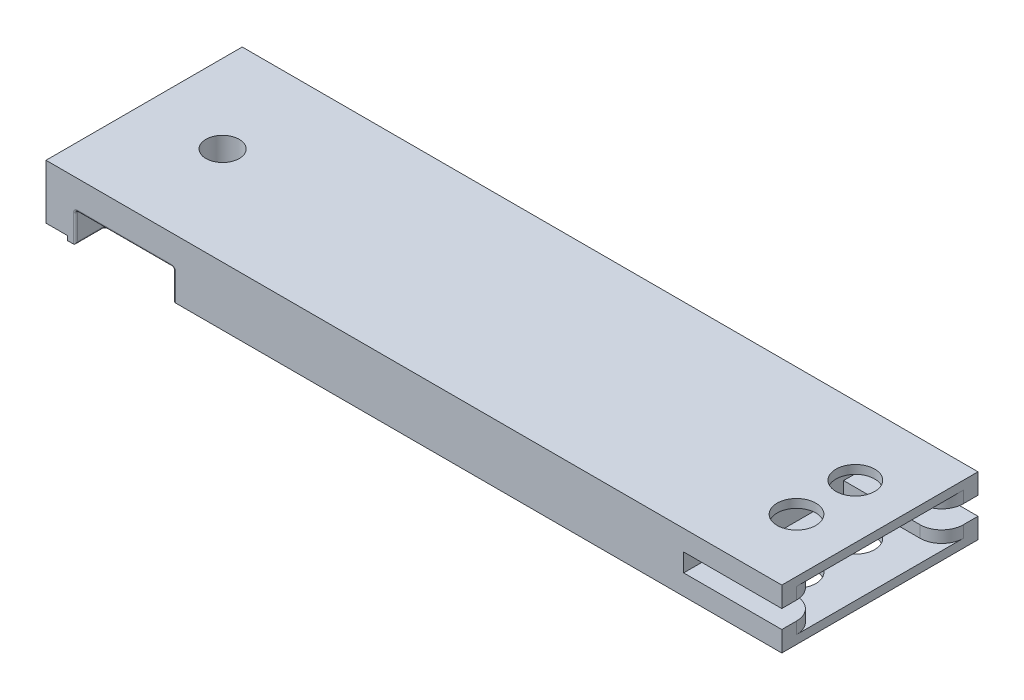
SolidWorks part; units mm, degrees
ref_plane "Front Plane" through (0, 0, 0) normal (0, 0, 1) x (1, 0, 0)
ref_plane "Top Plane" through (0, 0, 0) normal (0, 1, 0) x (1, 0, 0)
ref_plane "Right Plane" through (0, 0, 0) normal (1, 0, 0) x (0, 0, -1)
sketch "Sketch1" plane through (0, 0, 0) normal (1, 0, 0) x (0, 0, -1)
  line L1 (-10, -6) -> (10, -6)
  line L2 (-10, -6) -> (-10, 0)
  line L3 (-10, 0) -> (10, 0)
  line L4 (10, -6) -> (10, 0)
  line L5 (-10, -6) -> (10, 0) construction
  line L6 (-10, 0) -> (10, -6) construction
  point P0 (0, -3)
  dimension "D1" = 20
  dimension "D2" = 6
extrude "Boss-Extrude1" add sketch "Sketch1" along normal blind 75
hole_wizard "M3 Clearance Hole1" positions "Sketch2" profile "Sketch3" hole size "M3" standard "ISO" end condition through all
sketch "Sketch2" plane through (0, 0, 0) normal (0, 1, 0) x (1, 0, 0)
  line L0 (0, 10) -> (0, -10) construction
  point P0 (8, 0)
  dimension "D1" = 8
sketch "Sketch3" plane through (8, 0, 0) normal (1, 0, 0) x (0, 0, 1)
  line L0 (0, 0) -> (0, 6)
  line L1 (0, 6) -> (1.7, 6)
  line L2 (1.7, 6) -> (1.7, 0)
  line L5 (1.7, 0) -> (0, 0)
  line L11 (0, -6.35) -> (0, 107.95) construction
  dimension "Thru Hole Dia." = 3.4
  dimension "Thru Hole Depth" = 6
sketch "Sketch4" plane through (0, 0, 0) normal (0, 1, 0) x (1, 0, 0)
  line L13 (75, 10) -> (75, -10) construction
  circle A0 centre (69.5, 3) radius 1.975
  circle A1 centre (69.5, -3) radius 1.975
  point P10 (69.5, -3)
  point P18 (69.5, 3)
  dimension "D5" = 3.95
  dimension "D6" = 3.95
  dimension "D1" = 5.5
  dimension "D2" = 6
  dimension "D3" = 3
extrude "Cut-Extrude1" cut sketch "Sketch4" against normal through all
sketch "Sketch5" plane through (75, 0, 0) normal (1, 0, 0) x (0, 0, -1)
  line L0 (10, -6) -> (10, 0) construction
  line L1 (-10, -3.925) -> (-6.3, -3.925)
  line L2 (-10, -3.925) -> (-10, -2.075)
  line L3 (-10, -2.075) -> (-6.3, -2.075)
  line L4 (10, -3.925) -> (10, -2.075)
  line L7 (-10, 0) -> (-10, -6) construction
  line L8 (-6.3, -5.125) -> (6.3, -5.125)
  line L9 (-6.3, -5.125) -> (-6.3, -3.925)
  line L10 (-6.3, -0.875) -> (6.3, -0.875)
  line L11 (6.3, -5.125) -> (6.3, -3.925)
  line L15 (-6.3, -2.075) -> (-6.3, -0.875)
  line L18 (6.3, -2.075) -> (10, -2.075)
  line L20 (6.3, -3.925) -> (10, -3.925)
  line L21 (6.3, -2.075) -> (6.3, -0.875)
  point P0 (0, -3)
  point P7 (0, -3)
  point P12 (10, -3)
  point P17 (-10, -3)
  dimension "D1" = 12.6
  dimension "D2" = 1.85
  dimension "D3" = 3
  dimension "D4" = 4.25
extrude "Cut-Extrude2" cut sketch "Sketch5" against normal blind 10
sketch "Sketch6" plane through (0, -6, 0) normal (0, -1, 0) x (1, 0, 0)
  line L0 (75, 10) -> (0, 10) construction
  line L1 (3, 10) -> (13, 10)
  line L2 (3, 10) -> (3, 7)
  line L3 (3, 7) -> (13, 7)
  line L4 (13, 10) -> (13, 7)
  line L5 (75, -10) -> (0, -10) construction
  line L6 (13, -10) -> (3, -10)
  line L7 (13, -10) -> (13, -7)
  line L8 (13, -7) -> (3, -7)
  line L9 (3, -10) -> (3, -7)
  line L10 (0, 10) -> (0, -10) construction
  dimension "D1" = 3
  dimension "D2" = 10
  dimension "D3" = 3
extrude "Cut-Extrude3" cut sketch "Sketch6" against normal blind 3
fillet "Fillet1" radius 0.2 22 edges at (13, -6, -8.5) (3, -6, -8.5) (3, -4.5, -10) (13, -4.5, -10) (13, -4.5, -7) (3, -4.5, -7) (8, -6, -7) (8, -3, -10) (3, -3, -8.5) (8, -3, -7) (13, -3, -8.5) (3, -6, 8.5) (13, -6, 8.5) (13, -4.5, 10) (3, -4.5, 10) (3, -4.5, 7) (13, -4.5, 7) (8, -6, 7) (8, -3, 10) (13, -3, 8.5) (8, -3, 7) (3, -3, 8.5)
fillet "Fillet2" radius 2.2 4 edges at (75, -4.525, -6.3) (75, -4.525, 6.3) (75, -1.475, -6.3) (75, -1.475, 6.3)
sketch "Sketch7" plane through (0, -6, 0) normal (0, -1, 0) x (1, 0, 0)
  line L9 (2.55, 10) -> (13.45, 10)
  line L10 (0, 0) -> (75, 0) construction
  line L12 (13.45, 10) -> (13.45, 7.2)
  line L13 (12.8, 6.55) -> (3.2, 6.55)
  line L14 (2.55, 7.2) -> (2.55, 10)
  line L15 (13.45, 10) -> (13.45, 7.2)
  line L16 (12.8, 6.55) -> (3.2, 6.55)
  line L17 (2.55, 7.2) -> (2.55, 10)
  line L18 (2.55, -7.2) -> (2.55, -10)
  line L19 (12.8, -6.55) -> (3.2, -6.55)
  line L20 (13.45, -10) -> (13.45, -7.2)
  line L21 (2.55, -10) -> (13.45, -10)
  arc A6 (2.55, -7.2) -> (3.2, -6.55) centre (3.2, -7.2) cw
  arc A7 (12.8, -6.55) -> (13.45, -7.2) centre (12.8, -7.2) cw
  arc A8 (12.8, 6.55) -> (13.45, 7.2) centre (12.8, 7.2) ccw
  arc A9 (2.55, 7.2) -> (3.2, 6.55) centre (3.2, 7.2) ccw
  arc A10 (12.8, 6.55) -> (13.45, 7.2) centre (12.8, 7.2) ccw
  arc A11 (2.55, 7.2) -> (3.2, 6.55) centre (3.2, 7.2) ccw
  dimension "D1" = 0.25
extrude "3DP" [suppressed] cut sketch "Sketch7" against normal blind 3.5
fillet "3DP2" [suppressed] radius 0.2
sketch "Sketch8" plane through (0, 0, 0) normal (0, 1, 0) x (1, 0, 0)
  circle A2 centre (8, 0) radius 1.95
  circle A3 centre (8, 0) radius 1.95
  circle A10 centre (69.5, 3) radius 2.225
  circle A11 centre (69.5, 3) radius 2.225
  circle A13 centre (69.5, -3) radius 2.225
  circle A14 centre (69.5, -3) radius 2.225
  dimension "D1" = 0.25
  dimension "D2" = 0.25
  dimension "D3" = 0.25
extrude "3DP3" [suppressed] cut sketch "Sketch8" against normal through all
sketch "Sketch9" plane through (75, 0, 0) normal (1, 0, 0) x (0, 0, -1)
  line L3 (-6.3, -0.875) -> (-6.3, -2.075) construction
  line L10 (-10, -2.075) -> (-6.3, -2.075)
  line L11 (-6.3, -2.075) -> (-10, -2.075) construction
  line L12 (-6.3, -2.075) -> (-6.3, -0.875)
  line L13 (-6.3, -0.875) -> (6.3, -0.875)
  line L14 (8.5, -0.875) -> (-8.5, -0.875) construction
  line L15 (6.3, -0.875) -> (8.5, -0.875) construction
  line L16 (6.3, -0.875) -> (6.3, -2.075)
  line L17 (6.3, -2.075) -> (10, -2.075)
  line L18 (10, -2.075) -> (10, -3.925)
  line L19 (10, -3.925) -> (6.3, -3.925)
  line L20 (6.3, -3.925) -> (6.3, -5.125)
  line L21 (-8.5, -5.125) -> (8.5, -5.125) construction
  line L22 (6.3, -5.125) -> (6.3, -3.925) construction
  line L23 (6.3, -5.125) -> (-6.3, -5.125)
  line L24 (-6.3, -5.125) -> (-8.5, -5.125) construction
  line L25 (-6.3, -5.125) -> (-6.3, -3.925)
  line L26 (-6.3, -3.925) -> (-10, -3.925)
  line L27 (-10, -3.925) -> (-10, -2.075)
  line L28 (-10.35, -1.725) -> (-6.65, -1.725)
  line L29 (-6.65, -1.725) -> (-6.65, -0.525)
  line L30 (-6.65, -0.525) -> (6.65, -0.525)
  line L31 (6.65, -0.525) -> (6.65, -1.725)
  line L32 (6.65, -1.725) -> (10.35, -1.725)
  line L33 (10.35, -1.725) -> (10.35, -4.275)
  line L34 (10.35, -4.275) -> (6.65, -4.275)
  line L35 (6.65, -4.275) -> (6.65, -5.475)
  line L36 (6.65, -5.475) -> (-6.65, -5.475)
  line L37 (-6.65, -5.475) -> (-6.65, -4.275)
  line L38 (-6.65, -4.275) -> (-10.35, -4.275)
  line L39 (-10.35, -4.275) -> (-10.35, -1.725)
  line M13 (-8.5, -0.875) -> (8.5, -0.875)
  line M15 (8.5, -2.075) -> (10, -2.075)
  line M19 (-10, -2.075) -> (-8.5, -2.075)
  dimension "D1" = 0.35
extrude "3DP4" [suppressed] cut sketch "Sketch9" against normal blind 10.55 contours L27 L26 L25 L23 L20 L19 L18 L17 L16 L12 L10 M15 M13 M19
sketch "Sketch10" plane through (0, -5.125, 0) normal (0, 1, 0) x (1, 0, 0)
  line L0 (72.8, 6.5) -> (64.8, 6.5)
  line L1 (64.8, 6.5) -> (64.8, -6.5)
  line L2 (64.8, -6.5) -> (72.8, -6.5)
  line L3 (74.8, 8.5) -> (75, 8.5)
  line L4 (75, -8.5) -> (75, 8.5)
  line L5 (72.8, 6.3) -> (65, 6.3)
  line L6 (65, 6.3) -> (65, -6.3)
  line L7 (65, -6.3) -> (72.8, -6.3)
  line L9 (72.8, 6.3) -> (65, 6.3)
  line L11 (65, -6.3) -> (72.8, -6.3)
  line L12 (75, -8.5) -> (74.8, -8.5)
  line L17 (65, 6.3) -> (65, -6.3) construction
  line L20 (65, 6.3) -> (65, -6.3)
  arc A0 (72.8, 6.5) -> (74.8, 8.5) centre (72.8, 8.5) ccw
  arc A1 (74.8, -8.5) -> (72.8, -6.5) centre (72.8, -8.5) ccw
  arc A2 (72.8, 6.3) -> (75, 8.5) centre (72.8, 8.5) ccw
  arc A3 (75, -8.5) -> (72.8, -6.3) centre (72.8, -8.5) ccw
  arc A4 (72.8, 6.3) -> (75, 8.5) centre (72.8, 8.5) ccw
  arc A5 (75, -8.5) -> (72.8, -6.3) centre (72.8, -8.5) ccw
  dimension "D1" = 0
  dimension "D2" = 0.2
extrude "3DP5" [suppressed] cut sketch "Sketch10" along normal up to surface (4.25 mm away)
sketch "Sketch12" plane through (0, 0, 0) normal (-1, 0, 0) x (0, 0, 1)
  line L0 (-10, -6) -> (-10, 0) construction
  line L1 (-10, 0) -> (10, 0)
  line L2 (-10, 0) -> (-10, -6)
  line L3 (-10, -6) -> (10, -6)
  line L4 (10, 0) -> (10, -6)
  circle A0 centre (0, -21) radius 18.4
  line M3 (-10, -6) -> (10, -6)
  line M4 (10, -6) -> (10, 0)
  dimension "D1" = 36.8
  dimension "D2" = 21
extrude "Cut-Extrude5" cut sketch "Sketch12" against normal blind 2.2 contours A0 L2 M4 M3
